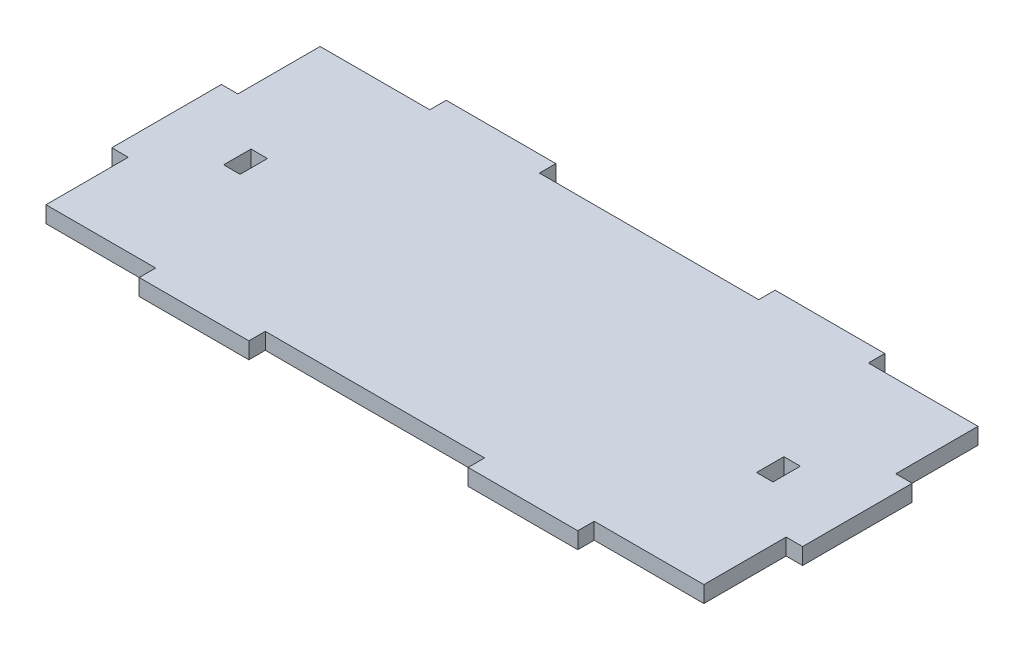
SolidWorks part; units mm, degrees
ref_plane "Front Plane" through (0, 0, 0) normal (0, 0, 1) x (1, 0, 0)
ref_plane "Top Plane" through (0, 0, 0) normal (0, 1, 0) x (1, 0, 0)
ref_plane "Right Plane" through (0, 0, 0) normal (1, 0, 0) x (0, 0, -1)
sketch "Sketch2" plane through (0, 0, 0) normal (0, 1, 0) x (1, 0, 0)
  line L0 (0, 50) -> (0, 35) construction
  line L1 (0, 0) -> (20, 0)
  line L2 (0, 0) -> (0, 15)
  line L3 (0, 50) -> (20, 50)
  line L4 (120, 0) -> (120, 15)
  line L5 (0, 50) -> (20, 50) construction
  line L6 (0, 15) -> (-3, 15)
  line L8 (0, 35) -> (-3, 35)
  line L9 (-3, 15) -> (-3, 35)
  line L10 (40, 50) -> (80, 50)
  line L11 (40, 50) -> (80, 50) construction
  line L12 (60, 50) -> (40, 50) construction
  line L13 (100, 0) -> (120, 0)
  line L14 (20, 53) -> (40, 53)
  line L15 (20, 53) -> (20, 50)
  line L17 (40, 53) -> (40, 50)
  line L18 (40, 0) -> (80, 0)
  line L19 (80, -3) -> (80, 0)
  line L20 (0, 50) -> (9.9, 50) construction
  line L21 (40, -3) -> (40, 0)
  line L23 (20, -3) -> (20, 0)
  line L24 (20, -3) -> (40, -3)
  line L25 (0, 15) -> (0, 0) construction
  line L26 (0, 35) -> (0, 50)
  line L27 (20, 50) -> (0, 50) construction
  line L28 (100, -3) -> (80, -3)
  line L29 (100, -3) -> (100, 0)
  line L30 (120, 15) -> (123, 15)
  line L31 (123, 15) -> (123, 35)
  line L32 (120, 35) -> (123, 35)
  line L33 (100, 53) -> (100, 50)
  line L34 (80, 53) -> (80, 50)
  line L35 (100, 53) -> (80, 53)
  line L36 (100, 50) -> (120, 50)
  line L37 (100, 50) -> (120, 50) construction
  line L38 (120, 35) -> (120, 50)
  line L39 (9.9, 50) -> (9.9, 27.5) construction
  line L40 (60, 50) -> (60, 0) construction
  line L41 (9.9, 27.5) -> (12.9, 27.5)
  line L42 (9.9, 27.5) -> (9.9, 22.5)
  line L43 (9.9, 22.5) -> (12.9, 22.5)
  line L44 (12.9, 27.5) -> (12.9, 22.5)
  line L45 (110.1, 22.5) -> (107.1, 22.5)
  line L46 (107.1, 27.5) -> (107.1, 22.5)
  line L47 (110.1, 27.5) -> (107.1, 27.5)
  line L48 (110.1, 27.5) -> (110.1, 22.5)
  point P4 (0, 25)
  point P11 (30, 50)
  dimension "D1" = 120
  dimension "D2" = 50
  dimension "D3" = 5
  dimension "D4" = 22.5
  dimension "2" = 20
  dimension "D5" = 20
  dimension "D6" = 20
  dimension "D7" = 20
  dimension "D8" = 20
  dimension "D9" = 3
extrude "Boss-Extrude1" add sketch "Sketch2" along normal blind 3
